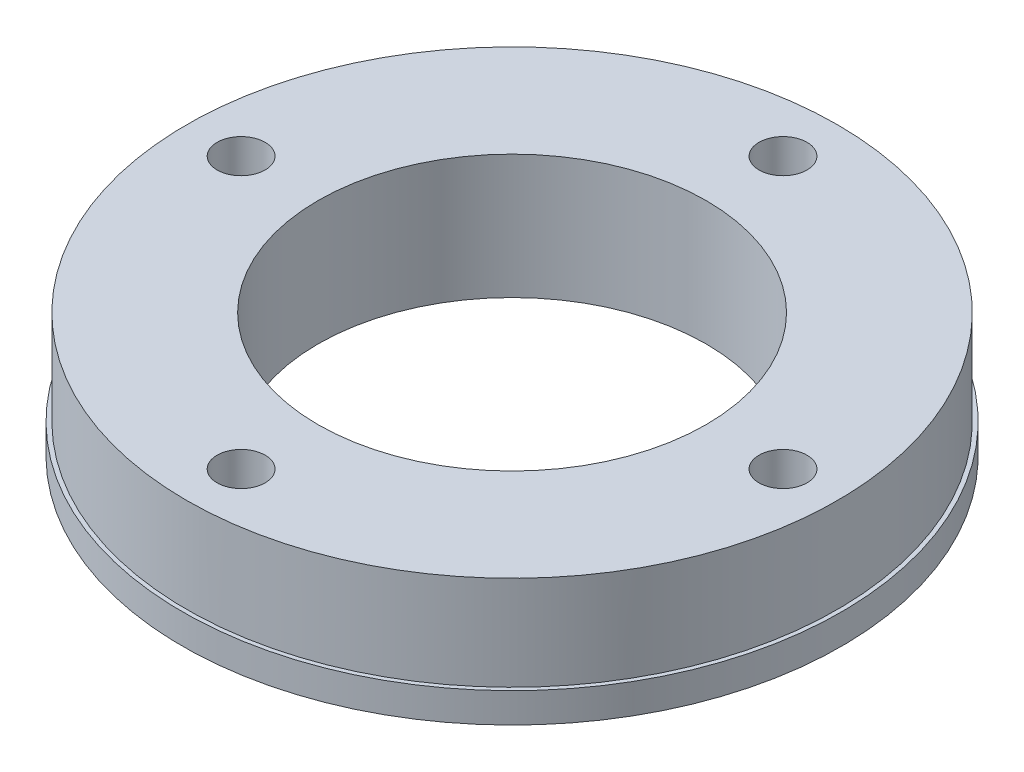
SolidWorks part; units mm, degrees
ref_plane "Front Plane" through (0, 0, 0) normal (0, 0, 1) x (1, 0, 0)
ref_plane "Top Plane" through (0, 0, 0) normal (0, 1, 0) x (1, 0, 0)
ref_plane "Right Plane" through (0, 0, 0) normal (1, 0, 0) x (0, 0, -1)
sketch "Sketch1" plane through (0, 0, 0) normal (0, 1, 0) x (1, 0, 0)
  line L0 (-37.9882, 0) -> (33.7078, 0) construction
  line L1 (0, -33.2919) -> (0, 34.04) construction
  circle A0 centre (0, 0) radius 25.273
  circle A1 centre (0, 0) radius 14.8831
  circle A2 centre (0, 20.7772) radius 1.8415
  circle A3 centre (0, -20.7772) radius 1.8415
  circle A4 centre (20.7772, 0) radius 1.8415
  circle A5 centre (-20.7772, 0) radius 1.8415
  dimension "D1" = 50.546
  dimension "D2" = 29.7663
  dimension "D3" = 20.7772
  dimension "D4" = 3.683
extrude "Extrude1" add sketch "Sketch1" along normal blind 9.525
sketch "Sketch2" plane through (0, 0, 0) normal (1, 0, 0) x (0, 0, -1)
  line L0 (-30.0494, 2.286) -> (-24.9555, 2.286)
  line L1 (-24.9555, 2.286) -> (-24.9555, 13.5798)
  line L2 (-24.9555, 13.5798) -> (-30.0494, 13.5798)
  line L3 (-30.0494, 13.5798) -> (-30.0494, 2.286)
  line L4 (0, 0) -> (0, 33.476) construction
  dimension "D1" = 2.286
  dimension "D2" = 24.9555
revolve "Cut-Revolve1" cut sketch "Sketch2" angle 360 about L4
